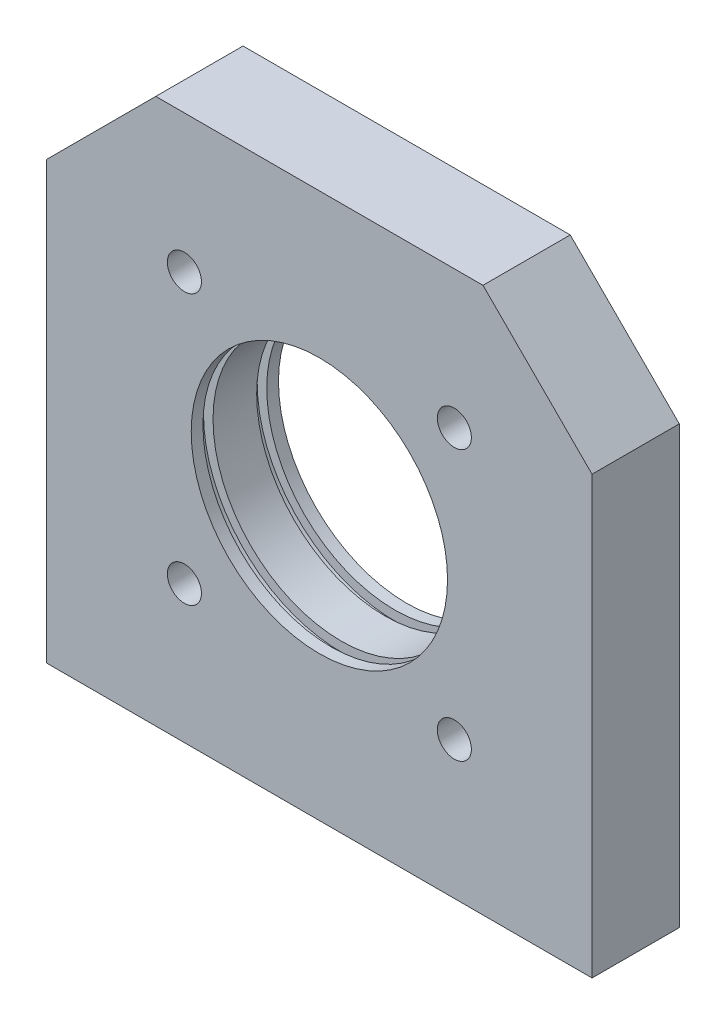
SolidWorks part; units mm, degrees
ref_plane "Front Plane" through (0, 0, 0) normal (0, 0, 1) x (1, 0, 0)
ref_plane "Top Plane" through (0, 0, 0) normal (0, 1, 0) x (1, 0, 0)
ref_plane "Right Plane" through (0, 0, 0) normal (1, 0, 0) x (0, 0, -1)
sketch "Sketch1" plane through (0, 0, 0) normal (0, 0, 1) x (1, 0, 0)
  line L1 (-50, -50) -> (50, -50)
  line L2 (-50, -50) -> (-50, 50)
  line L3 (-50, 50) -> (50, 50)
  line L4 (50, -50) -> (50, 50)
  line L5 (-50, -50) -> (50, 50) construction
  line L6 (-50, 50) -> (50, -50) construction
  point P0 (0, 0)
  dimension "D1" = 100
extrude "Boss-Extrude1" add sketch "Sketch1" along normal blind 16
sketch "Sketch2" plane through (0, 0, 16) normal (0, 0, 1) x (1, 0, 0)
  circle A0 centre (0, 0) radius 23.5
  dimension "D1" = 47
extrude "Cut-Extrude1" cut sketch "Sketch2" against normal through all and the other way through all
ref_plane "Plane1" through (0, 0, 0) normal (1, 0, 0) x (0, 0, -1)
sketch "Sketch3" plane through (0, 0, 0) normal (1, 0, 0) x (0, 0, -1)
  line L0 (0, 23.5) -> (-2.15, 23.5)
  line L1 (0, -50) -> (0, 50) construction
  line L2 (-2.15, 23.5) -> (-2.15, 25.25)
  line L3 (-2.15, 25.25) -> (-4, 25.25)
  line L4 (-4, 25.25) -> (-4, 23.5)
  line L5 (-4, 23.5) -> (-12, 23.5)
  line L6 (-12, 23.5) -> (-12, 25.25)
  line L7 (-12, 25.25) -> (-13.85, 25.25)
  line L8 (-13.85, 25.25) -> (-13.85, 23.5)
  line L9 (-13.85, 23.5) -> (-16, 23.5)
  line L10 (-16, -50) -> (-16, 50) construction
  line L11 (0, 0) -> (-17.5734, 0) construction
  line L12 (-2.15, 23.5) -> (-4, 23.5)
  line L13 (-12, 23.5) -> (-13.85, 23.5)
  dimension "D1" = 25.25
  dimension "D2" = 23.5
  dimension "D3" = 1.85
  dimension "D4" = 8
revolve "Cut-Revolve1" cut sketch "Sketch3" angle 360 about L11
hole_wizard "Tap Drill for M6 Helicoil1" positions "Sketch5" profile "Sketch6" hole size "M6x1.0" standard "DIN"
sketch "Sketch5" plane through (0, -50, 0) normal (0, -1, 0) x (-1, 0, 0)
  line L0 (-40, -8) -> (-50, -8) construction
  line L1 (-50, -16) -> (-50, 0) construction
  line L8 (-50, -16) -> (50, -16) construction
  line L12 (40, -8) -> (50, -8) construction
  line L13 (50, -16) -> (50, 0) construction
  point P0 (-40, -8)
  point P61 (0, -8)
  point P62 (40, -8)
  dimension "D1" = 100
sketch "Sketch6" plane through (40, -50, 8) normal (1, 0, 0) x (0, 0, -1)
  line L0 (0, 0) -> (0, 16.8777)
  line L1 (0, 16.8777) -> (3.125, 15)
  line L2 (3.125, 15) -> (3.125, 0)
  line L5 (3.125, 0) -> (0, 0)
  line L10 (0, 16.8777) -> (-3.125, 15) construction
  line L11 (0, -6.35) -> (0, 107.95) construction
  dimension "Hole Dia." = 6.25
  dimension "Hole Depth" = 15
  dimension "Drill Angle" = 118
hole_wizard "Tap Drill for M6 Helicoil2" positions "Sketch7" profile "Sketch9" hole size "M6x1.0" standard "DIN" end condition through all
sketch "Sketch7" plane through (0, 0, 0) normal (0, 0, -1) x (-1, 0, 0)
  line L0 (0, 0) -> (0, 9.8364) construction
  line L2 (-24.7487, 24.7487) -> (0, 0) construction
  circle A0 centre (0, 0) radius 35 construction
  point P6 (-24.7487, 24.7487)
  point P13 (24.7487, 24.7487)
  point P14 (24.7487, -24.7487)
  point P15 (-24.7487, -24.7487)
  dimension "D1" = 70
  dimension "D2" = 4
  dimension "D3" = 45
sketch "Sketch9" plane through (24.7487, -24.7487, 0) normal (1, 0, 0) x (0, 1, 0)
  line L0 (0, 0) -> (0, 16)
  line L1 (0, 16) -> (3.125, 16)
  line L2 (3.125, 16) -> (3.125, 0)
  line L5 (3.125, 0) -> (0, 0)
  line L11 (0, -6.35) -> (0, 107.95) construction
  dimension "Thru Hole Dia." = 6.25
  dimension "Thru Hole Depth" = 16
hole_wizard "Tap Drill for M4 Tap1" positions "Sketch10" profile "Sketch11" hole size "M4" standard "DIN"
sketch "Sketch10" plane through (0, 0, 0) normal (0, 0, -1) x (-1, 0, 0)
  circle A2 centre (0, 0) radius 37.5 construction
  circle A3 centre (0, 0) radius 45 construction
  point P9 (0, 37.5)
  point P16 (32.476, -18.75)
  point P17 (-32.476, -18.75)
  point P44 (45, 0)
  point P52 (22.5, -38.9711)
  point P53 (-22.5, -38.9711)
  point P54 (-45, 0)
  point P55 (-22.5, 38.9711)
  point P56 (22.5, 38.9711)
  dimension "D1" = 3
  dimension "D2" = 75
  dimension "D3" = 90
sketch "Sketch11" plane through (-22.5, 38.9711, 0) normal (1, 0, 0) x (0, 1, 0)
  line L0 (0, 0) -> (0, 16)
  line L1 (0, 16) -> (1.65, 16)
  line L2 (1.65, 16) -> (1.65, 0)
  line L5 (1.65, 0) -> (0, 0)
  line L11 (0, -6.35) -> (0, 107.95) construction
  dimension "Thru Hole Dia." = 3.3
  dimension "Thru Hole Depth" = 16
chamfer "Chamfer1" distance 20 angle 45 2 edges at (-50, 50, 8) (50, 50, 8)
